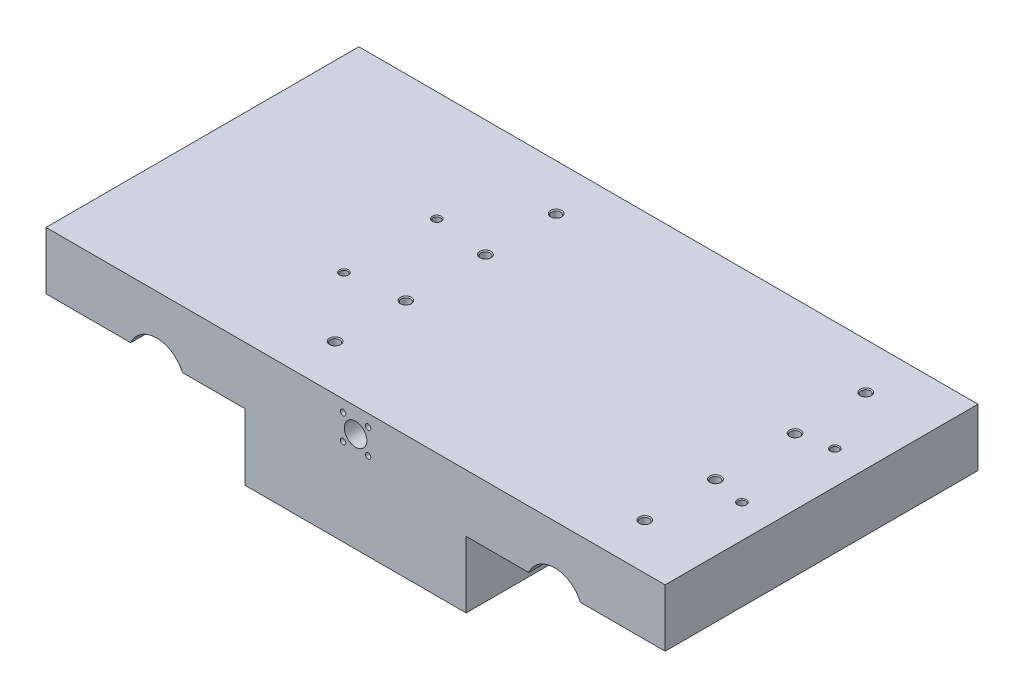
SolidWorks part; units mm, degrees
material "Ceramic Porcelain"
ref_plane "Front Plane" through (0, 0, 0) normal (0, 0, 1) x (1, 0, 0)
ref_plane "Top Plane" through (0, 0, 0) normal (0, 1, 0) x (1, 0, 0)
ref_plane "Right Plane" through (0, 0, 0) normal (1, 0, 0) x (0, 0, -1)
sketch "Sketch1" plane through (0, 0, 0) normal (0, 0, 1) x (1, 0, 0)
  line L0 (-140, 0) -> (-140, 26)
  line L1 (-140, 26) -> (140, 26)
  line L2 (140, 26) -> (140, 0)
  line L3 (140, 0) -> (101.6743, 0)
  line L4 (78.3257, 0) -> (-78.3257, 0)
  line L5 (-101.6743, 0) -> (-140, 0)
  line L6 (0, 0) -> (0, 26) construction
  circle A2 centre (0, 15) radius 5.1
  arc A3 (-101.6743, 0) -> (-78.3257, 0) centre (-90, -5) cw
  arc A4 (101.6743, 0) -> (78.3257, 0) centre (90, -5) ccw
  point P14 (0, 26)
  dimension "D1" = 10.2
  dimension "D2" = 20
  dimension "D3" = 12.7
  dimension "D4" = 180
  dimension "D5" = 280
  dimension "D6" = 5
  dimension "D7" = 26
extrude "Boss-Extrude1" add sketch "Sketch1" along normal mid plane 141.5
hole_wizard "Furo roscado de M5x0.81" positions "Esboço2" profile "Esboço3" tap size "M5x0.8" standard "Ansi Metric"
sketch "Esboço2" plane through (0, 26, 0) normal (0, 1, 0) x (1, 0, 0)
  line L1 (140, -70.75) -> (140, 70.75) construction
  line L2 (110, 18) -> (110, 50) construction
  point P0 (110, 50)
  point P2 (110, 18)
  point P17 (110, 34)
  dimension "D1" = 32
  dimension "D2" = 34
  dimension "D3" = 30
sketch "Esboço3" plane through (110, 26, -50) normal (1, 0, 0) x (0, 0, 1)
  line L0 (0, 0) -> (0, 15.2618)
  line L1 (0, 15.2618) -> (2.1, 14)
  line L2 (2.1, 14) -> (2.1, 0.425)
  line L3 (2.1, 0.425) -> (2.525, 0)
  line L5 (2.525, 0) -> (0, 0)
  line L6 (-2.1, 0.425) -> (-2.525, 0) construction
  line L10 (0, 15.2618) -> (-2.1, 14) construction
  line L11 (0, -6.35) -> (0, 107.95) construction
  dimension "Tap Drill Dia." = 4.2
  dimension "Tap Drill Depth" = 14
  dimension "Near C'Sink Dia." = 5.05
  dimension "Near C'Sink Angle" = 90
  dimension "Drill Angle" = 118
cosmetic thread "Rosca de furo1" parameters "D1"=10, "D2"=5
cosmetic thread "Rosca de furo2" parameters "D1"=10, "D2"=5
sketch "Sketch2" plane through (0, 0, 70.75) normal (0, 0, 1) x (1, 0, 0)
  line L0 (0, 15) -> (-5.6569, 20.6569) construction
  circle A0 centre (-5.6569, 20.6569) radius 1.25
  circle A1 centre (5.6569, 20.6569) radius 1.25
  circle A2 centre (5.6569, 9.3431) radius 1.25
  circle A3 centre (-5.6569, 9.3431) radius 1.25
  point P13 (0, 15)
  dimension "D2" = 2.5
  dimension "D1" = 45
  dimension "D4" = 8
  dimension "D3" = 4
hole_wizard "M3x0.5 Tapped Hole1" positions "Sketch3" profile "Sketch4" tap size "M3x0.5" standard "ANSI Metric"
sketch "Sketch3" plane through (0, 0, 70.75) normal (0, 0, 1) x (1, 0, 0)
  point P0 (-5.6569, 20.6569)
  point P3 (5.6569, 20.6569)
  point P6 (-5.6569, 9.3431)
  point P9 (5.6569, 9.3431)
sketch "Sketch4" plane through (-5.6569, 20.6569, 70.75) normal (1, 0, 0) x (0, -1, 0)
  line L0 (0, 0) -> (0, 13.2511)
  line L1 (0, 13.2511) -> (1.25, 12.5)
  line L2 (1.25, 12.5) -> (1.25, 0)
  line L5 (1.25, 0) -> (0, 0)
  line L10 (0, 13.2511) -> (-1.25, 12.5) construction
  line L11 (0, -6.35) -> (0, 107.95) construction
  dimension "Tap Drill Dia." = 2.5
  dimension "Tap Drill Depth" = 12.5
  dimension "Drill Angle" = 118
mirror "Mirror2" about plane through (0, 0, 0) normal (0, 0, 1) of "M3x0.5 Tapped Hole1"
sketch "Esboço4" plane through (140, 0, 0) normal (-1, 0, 0) x (0, 0, 1)
  line L1 (-70.75, 26) -> (70.75, 26)
  line L2 (-70.75, 26) -> (-70.75, 0)
  line L3 (-70.75, 0) -> (70.75, 0)
  line L4 (70.75, 26) -> (70.75, 0)
sketch "Esboço5" plane through (0, 26, 0) normal (0, 1, 0) x (1, 0, 0)
  line L0 (50.8465, 0) -> (-25.1786, 0) construction
  line L1 (-140, -70.75) -> (-140, 70.75) construction
  point P1 (-55, 21)
  point P4 (-55, -21)
  dimension "D1" = 42
  dimension "D2" = 85
hole_wizard "Furo roscado de M4x0.71" positions "Esboço6" profile "Esboço7" tap size "M4x0.7" standard "Ansi Metric"
sketch "Esboço6" plane through (0, 26, 0) normal (0, 1, 0) x (1, 0, 0)
  point P0 (-55, 21)
  point P3 (-55, -21)
sketch "Esboço7" plane through (-55, 26, -21) normal (1, 0, 0) x (0, 0, 1)
  line L0 (0, 0) -> (0, 12.4914)
  line L1 (0, 12.4914) -> (1.65, 11.5)
  line L2 (1.65, 11.5) -> (1.65, 0.375)
  line L3 (1.65, 0.375) -> (2.025, 0)
  line L5 (2.025, 0) -> (0, 0)
  line L6 (-1.65, 0.375) -> (-2.025, 0) construction
  line L10 (0, 12.4914) -> (-1.65, 11.5) construction
  line L11 (0, -6.35) -> (0, 107.95) construction
  dimension "Tap Drill Dia." = 3.3
  dimension "Tap Drill Depth" = 11.5
  dimension "Near C'Sink Dia." = 4.05
  dimension "Near C'Sink Angle" = 90
  dimension "Drill Angle" = 118
cosmetic thread "Rosca de furo9" parameters "D1"=8, "D2"=4
cosmetic thread "Rosca de furo10" parameters "D1"=8, "D2"=4
pattern_linear "Padrão linear1" count 2 spacing 180 along (1, 0, 0) of "Furo roscado de M4x0.71"
cosmetic thread "Rosca de furo11" parameters "D1"=8, "D2"=4
cosmetic thread "Rosca de furo12" parameters "D1"=8, "D2"=4
sketch "Sketch5" plane through (0, 0, 70.75) normal (0, 0, 1) x (1, 0, 0)
  line L0 (-78.3257, 0) -> (78.3257, 0) construction
  line L1 (-50, 0) -> (50, 0)
  line L2 (-50, 0) -> (-50, -30)
  line L3 (-50, -30) -> (50, -30)
  line L4 (50, 0) -> (50, -30)
  point P6 (0, -30)
  dimension "D1" = 100
  dimension "D2" = 30
extrude "Boss-Extrude2" add sketch "Sketch5" against normal up to surface (141.5 mm away) up to face at (-6.9069, 9.3431, -70.75)
pattern_linear "LPattern1" count 2 spacing 140 along (-1, 0, 0) of "Furo roscado de M5x0.81"
cosmetic thread "Hole Thread1" parameters "D1"=10, "D2"=5
cosmetic thread "Hole Thread2" parameters "D1"=10, "D2"=5
mirror "Mirror3" about plane through (0, 0, 0) normal (0, 0, 1) of "LPattern1", "Furo roscado de M5x0.81"
cosmetic thread "Hole Thread3" parameters "D1"=10, "D2"=5
cosmetic thread "Hole Thread4" parameters "D1"=10, "D2"=5
cosmetic thread "Hole Thread5" parameters "D1"=10, "D2"=5
cosmetic thread "Hole Thread6" parameters "D1"=10, "D2"=5
